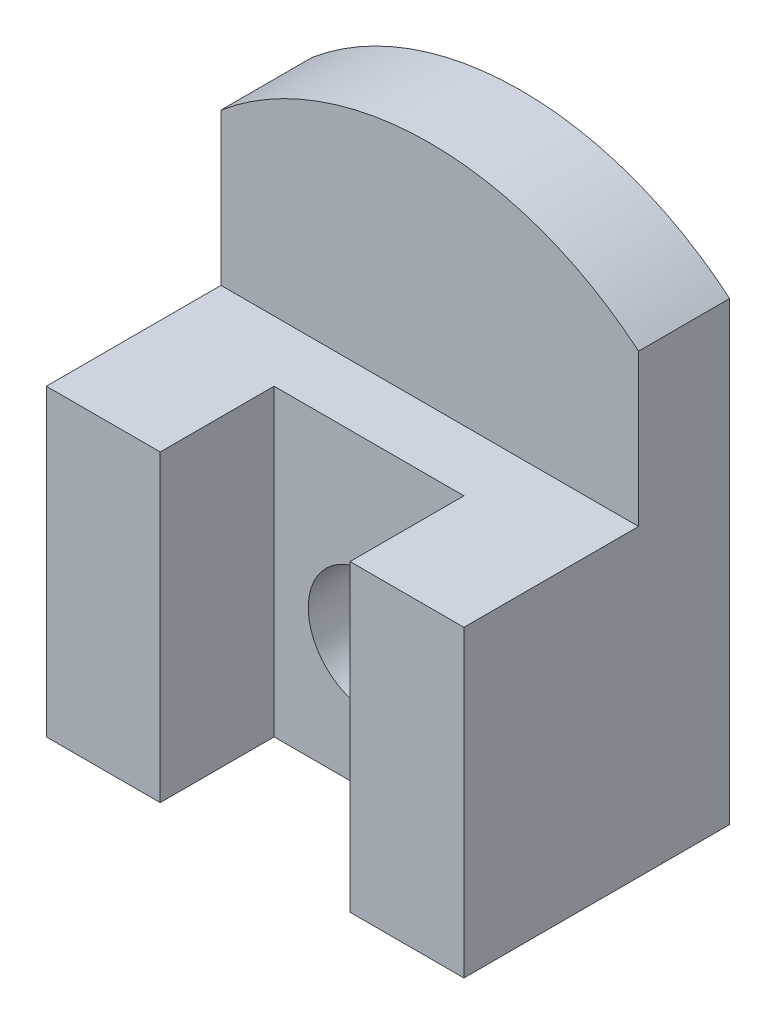
SolidWorks part; units mm, degrees
ref_plane "Plan1" through (0, 0, 0) normal (0, 0, 1) x (1, 0, 0)
ref_plane "Plan2" through (0, 0, 0) normal (0, 1, 0) x (1, 0, 0)
ref_plane "Plan3" through (0, 0, 0) normal (1, 0, 0) x (0, 0, -1)
sketch "Esquisse1" plane through (0, 0, 0) normal (0, 0, 1) x (1, 0, 0)
  line L0 (-60, 0) -> (-60, -60)
  line L1 (-60, -60) -> (-5, -60)
  line L2 (-5, -60) -> (-5, 0)
  line L3 (-100, 10) -> (40, 10) construction
  arc A0 (-5, 0) -> (-60, 0) centre (-32.5, -32.8125) ccw
  dimension "D4" = 70
  dimension "D1" = 55
  dimension "D2" = 60
  dimension "D3" = 60
extrude "Base-Extrusion" add sketch "Esquisse1" along normal blind 35
sketch "Esquisse5" plane through (-60, 0, 0) normal (-1, 0, 0) x (0, 0, 1)
  line L0 (12, 10) -> (12, -20)
  line L1 (12, -20) -> (42, -20)
  line L2 (42, -20) -> (42, 10)
  line L3 (12, 10) -> (42, 10)
  line L4 (0, 0) -> (0, -60) construction
  line L5 (35, -60) -> (0, -60) construction
  dimension "D1" = 12
  dimension "D2" = 40
extrude "Enlèv. mat.-Extru.5" cut sketch "Esquisse5" against normal through all
sketch "Esquisse6" plane through (0, -60, 0) normal (0, -1, 0) x (1, 0, 0)
  line L0 (-45, 40) -> (-45, 20)
  line L1 (-45, 20) -> (-20, 20)
  line L2 (-20, 20) -> (-20, 40)
  line L3 (-20, 40) -> (-45, 40)
  line L4 (-60, 35) -> (-60, 0) construction
  dimension "D1" = 25
  dimension "D2" = 15
extrude "Enlèv. mat.-Extru.6" cut sketch "Esquisse6" against normal through all
sketch "Esquisse7" plane through (0, 0, 20) normal (0, 0, 1) x (1, 0, 0)
  line L0 (-70, -43) -> (10, -43) construction
  line L1 (-32.5, 10) -> (-32.5, -60) construction
  line L3 (-5, 0) -> (-5, -20) construction
  line L4 (-60, -60) -> (-45, -60) construction
  circle A0 centre (-32.5, -43) radius 8
  dimension "D1" = 16
  dimension "D2" = 27.5
  dimension "D3" = 17
extrude "Enlèv. mat.-Extru.7" cut sketch "Esquisse7" against normal through all
